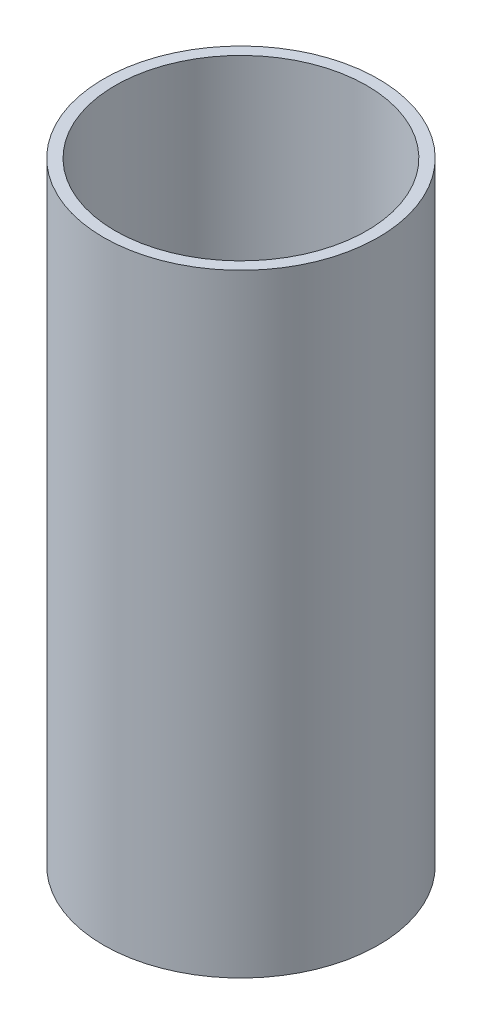
SolidWorks part; units mm, degrees
ref_plane "Front Plane" through (0, 0, 0) normal (0, 0, 1) x (1, 0, 0)
ref_plane "Top Plane" through (0, 0, 0) normal (0, 1, 0) x (1, 0, 0)
ref_plane "Right Plane" through (0, 0, 0) normal (1, 0, 0) x (0, 0, -1)
sketch "Sketch1" plane through (0, 0, 0) normal (0, 1, 0) x (1, 0, 0)
  circle A0 centre (0, 0) radius 19.05
  circle A1 centre (0, 0) radius 17.45
  dimension "D1" = 38.1
  dimension "D2" = 1.6
extrude "Boss-Extrude1" add sketch "Sketch1" along normal blind 85
